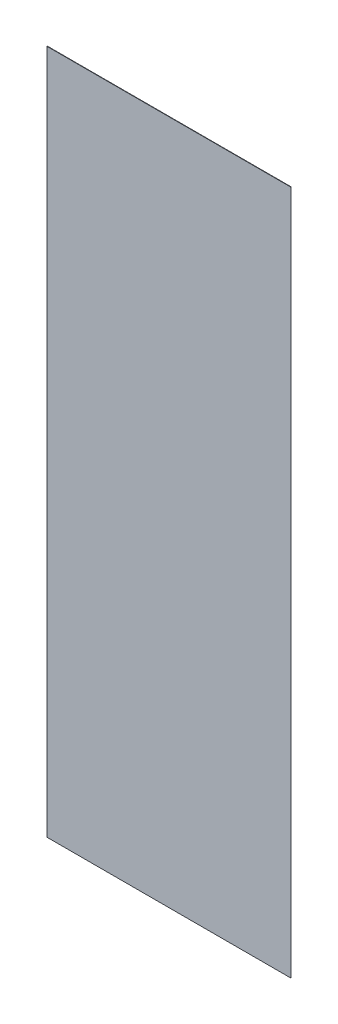
SolidWorks part; units mm, degrees
ref_plane "Front Plane" through (0, 0, 0) normal (0, 0, 1) x (1, 0, 0)
ref_plane "Top Plane" through (0, 0, 0) normal (0, 1, 0) x (1, 0, 0)
ref_plane "Right Plane" through (0, 0, 0) normal (1, 0, 0) x (0, 0, -1)
other "Configuration Table"
sketch "Sketch1" plane through (0, 0, 0) normal (0, 0, 1) x (1, 0, 0)
  line L1 (42.5, 241.5) -> (657.5, 241.5)
  line L2 (42.5, 241.5) -> (42.5, 1968.5)
  line L3 (42.5, 1968.5) -> (657.5, 1968.5)
  line L4 (657.5, 241.5) -> (657.5, 1968.5)
extrude "TOPPING_ic_arka_1" add sketch "Sketch1" against normal blind 1 from offset 797.5 separate body
